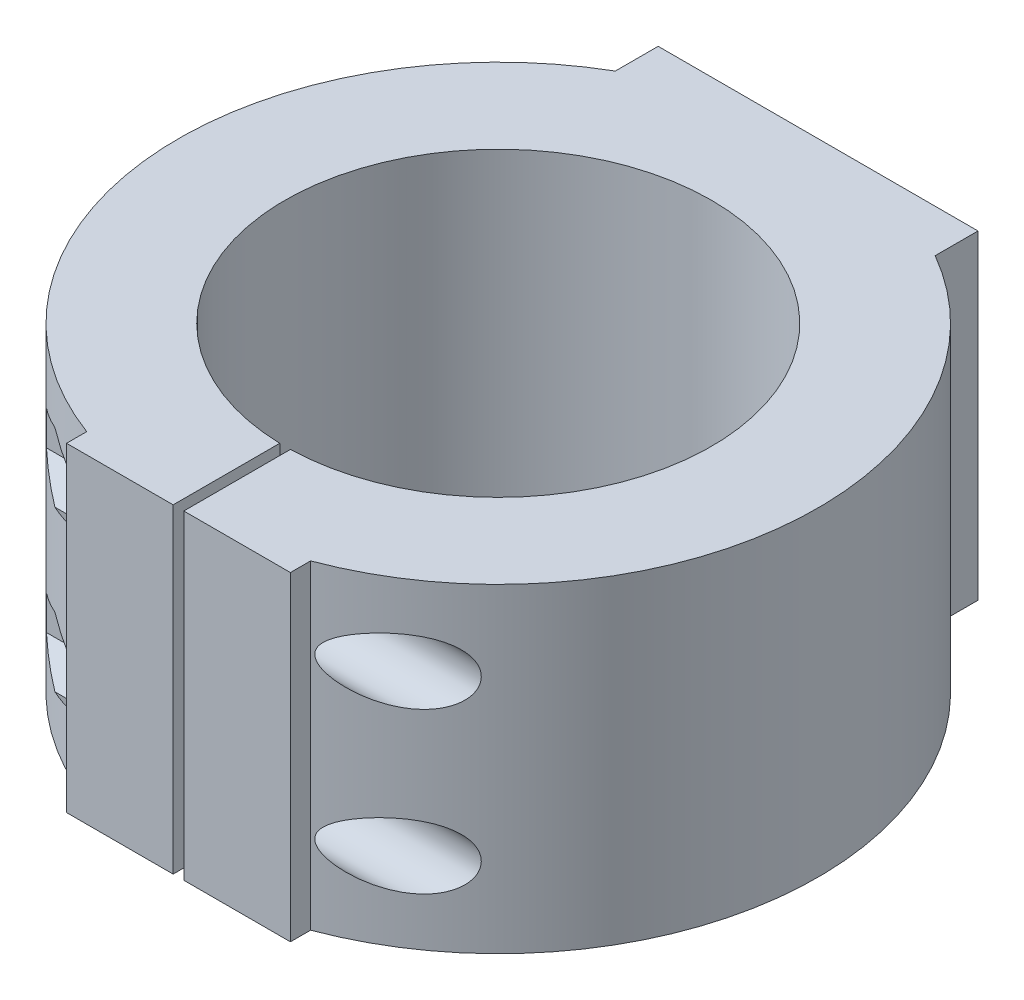
SolidWorks part; units mm, degrees
ref_plane "Front Plane" through (0, 0, 0) normal (0, 0, 1) x (1, 0, 0)
ref_plane "Top Plane" through (0, 0, 0) normal (0, 1, 0) x (1, 0, 0)
ref_plane "Right Plane" through (0, 0, 0) normal (1, 0, 0) x (0, 0, -1)
sketch "Sketch1" plane through (0, 0, 0) normal (0, 1, 0) x (1, 0, 0)
  line L0 (-0.5, -19.9937) -> (-0.5, -29.9937)
  line L1 (0.5, -19.9937) -> (0.5, -29.9937)
  line L2 (0, 20) -> (0, -19.9937) construction
  line L3 (-0.5, -19.9937) -> (0.5, -19.9937) construction
  line L4 (-0.5, -29.9937) -> (-10.5, -29.9937)
  line L5 (-10.5, -29.9937) -> (-10.5, -28.1025)
  line L6 (10.5, -28.1025) -> (10.5, -29.9937)
  line L7 (10.5, -29.9937) -> (0.5, -29.9937)
  line L8 (-15, 25.9808) -> (-15, 30)
  line L9 (-15, 30) -> (15, 30)
  line L10 (15, 30) -> (15, 25.9808)
  line L11 (0, 20) -> (0, 30) construction
  arc A0 (-15, 25.9808) -> (-10.5, -28.1025) centre (0, 0) ccw
  arc A1 (0.5, -19.9937) -> (-0.5, -19.9937) centre (0, 0) ccw
  arc A2 (15, 25.9808) -> (10.5, -28.1025) centre (0, 0) cw
  point P8 (0, -19.9937)
  point P13 (0, 0)
  dimension "D1" = 20
  dimension "D2" = 30
  dimension "D3" = 30
  dimension "D4" = 1
  dimension "D5" = 10
  dimension "D6" = 10
  dimension "D7" = 10
  dimension "D8" = 30
extrude "Boss-Extrude1" add sketch "Sketch1" along normal blind 30
ref_plane "Plane1" through (5, 0, 0) normal (-1, 0, 0) x (0, 0, 1)
ref_plane "Plane2" through (-5, 0, 0) normal (1, 0, 0) x (0, 0, -1)
sketch "Sketch7" plane through (5, 0, 0) normal (1, 0, 0) x (0, 0, -1)
  line L0 (-24.9937, 22.5) -> (-24.9937, 7.5) construction
  line L1 (-24.9937, 15) -> (-29.9937, 15) construction
  line L2 (-29.9937, 30) -> (-29.9937, 0) construction
  circle A0 centre (-24.9937, 22.5) radius 3
  circle A1 centre (-24.9937, 7.5) radius 3
  dimension "D3" = 6
  dimension "D1" = 5
  dimension "D2" = 15
extrude "Cut-Extrude1" cut sketch "Sketch7" along normal up to next
sketch "Sketch8" plane through (-5, 0, 0) normal (1, 0, 0) x (0, 0, -1)
  line L0 (-24.9937, 22.5) -> (-24.9937, 7.5) construction
  line L1 (-24.9937, 19.2668) -> (-22.1937, 20.8834)
  line L2 (-22.1937, 20.8834) -> (-22.1937, 24.1166)
  line L3 (-22.1937, 24.1166) -> (-24.9937, 25.7332)
  line L4 (-24.9937, 25.7332) -> (-27.7937, 24.1166)
  line L5 (-27.7937, 24.1166) -> (-27.7937, 20.8834)
  line L6 (-27.7937, 20.8834) -> (-24.9937, 19.2668)
  line L7 (-24.9937, 4.2668) -> (-22.1937, 5.8834)
  line L8 (-22.1937, 5.8834) -> (-22.1937, 9.1166)
  line L9 (-22.1937, 9.1166) -> (-24.9937, 10.7332)
  line L10 (-24.9937, 10.7332) -> (-27.7937, 9.1166)
  line L11 (-27.7937, 9.1166) -> (-27.7937, 5.8834)
  line L12 (-27.7937, 5.8834) -> (-24.9937, 4.2668)
  line L13 (-24.9937, 15) -> (-29.9937, 15) construction
  line L14 (-29.9937, 30) -> (-29.9937, 0) construction
  circle A0 centre (-24.9937, 22.5) radius 2.8 construction
  circle A1 centre (-24.9937, 7.5) radius 2.8 construction
  dimension "D1" = 5
  dimension "D2" = 15
  dimension "D3" = 5.6
extrude "Cut-Extrude2" cut sketch "Sketch8" against normal up to next
hole_wizard "M3 Clearance Hole1" positions "Sketch9" profile "Sketch10" hole size "M3" standard "ISO" end condition through all
sketch "Sketch9" plane through (5, 0, 0) normal (1, 0, 0) x (0, 0, -1)
  point P0 (-24.9937, 7.5)
  point P3 (-24.9937, 22.5)
sketch "Sketch10" plane through (5, 7.5, 24.9937) normal (0, 1, 0) x (0, 0, -1)
  line L0 (0, 0) -> (0, 35)
  line L1 (0, 35) -> (1.7, 35)
  line L2 (1.7, 35) -> (1.7, 0)
  line L5 (1.7, 0) -> (0, 0)
  line L11 (0, -6.35) -> (0, 107.95) construction
  dimension "Thru Hole Dia." = 3.4
  dimension "Thru Hole Depth" = 35
